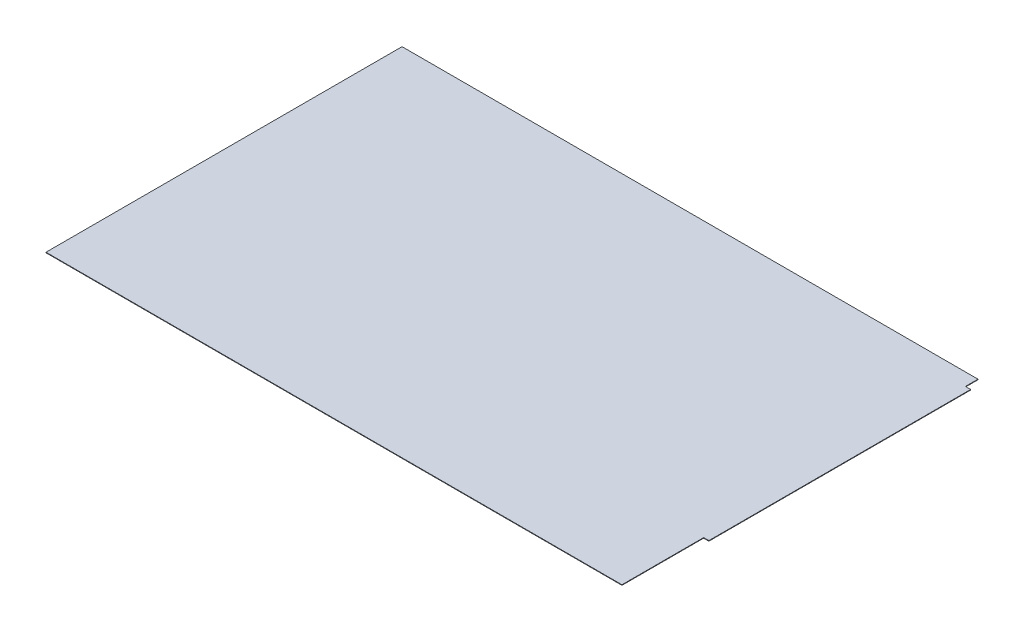
SolidWorks part; units mm, degrees
ref_plane "Front Plane" through (0, 0, 0) normal (0, 0, 1) x (1, 0, 0)
ref_plane "Top Plane" through (0, 0, 0) normal (0, 1, 0) x (1, 0, 0)
ref_plane "Right Plane" through (0, 0, 0) normal (1, 0, 0) x (0, 0, -1)
sketch "Sketch2" plane through (0, 0, 0) normal (0, 1, 0) x (1, 0, 0)
  line L1 (2750, -1700) -> (-2750, -1700)
  line L2 (2750, -1700) -> (2750, 1700)
  line L3 (2750, 1700) -> (-2750, 1700)
  line L4 (-2750, -1700) -> (-2750, 1700)
  line L5 (2750, -1700) -> (-2750, 1700) construction
  line L6 (2750, 1700) -> (-2750, -1700) construction
  point P0 (0, 0)
  dimension "D1" = 3400
  dimension "D2" = 5500
extrude "Boss-Extrude1" add sketch "Sketch2" along normal blind 5
sketch "Sketch3" plane through (0, 5, 0) normal (0, 1, 0) x (1, 0, 0)
  line L0 (2750, -1700) -> (2750, 1700) construction
  line L1 (2750, -920) -> (2800, -920)
  line L2 (2750, -920) -> (2750, 1580)
  line L3 (2750, 1580) -> (2800, 1580)
  line L4 (2800, -920) -> (2800, 1580)
  line L5 (2750, -920) -> (2800, 1580) construction
  line L6 (2750, 1580) -> (2800, -920) construction
  point P4 (2775, 330)
  dimension "D1" = 780
  dimension "D2" = 50
  dimension "D3" = 2500
extrude "Boss-Extrude2" add sketch "Sketch3" against normal blind 5
